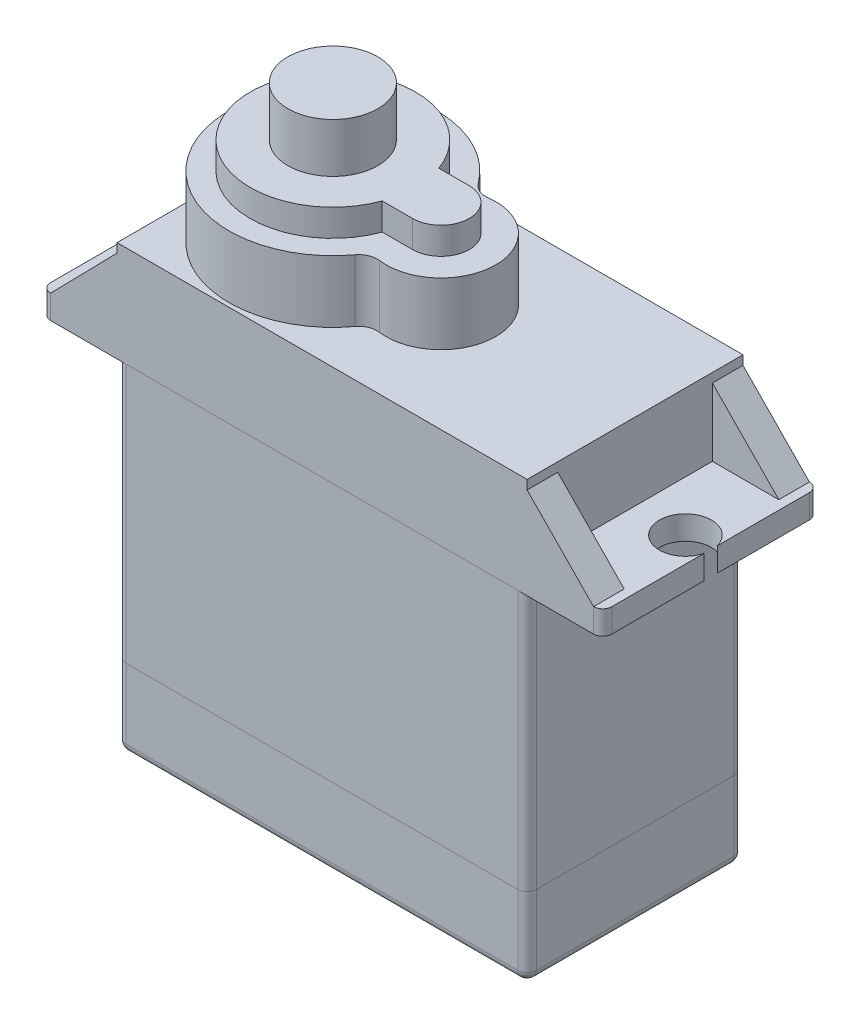
SolidWorks part; units mm, degrees
ref_plane "Front Plane" through (0, 0, 0) normal (0, 0, 1) x (1, 0, 0)
ref_plane "Top Plane" through (0, 0, 0) normal (0, 1, 0) x (1, 0, 0)
ref_plane "Right Plane" through (0, 0, 0) normal (1, 0, 0) x (0, 0, -1)
sketch "Sketch1" plane through (0, 0, 0) normal (0, 1, 0) x (1, 0, 0)
  line L1 (0, 0) -> (22.8, 0)
  line L2 (0, 0) -> (0, 12)
  line L3 (0, 12) -> (22.8, 12)
  line L4 (22.8, 0) -> (22.8, 12)
  dimension "D1" = 22.8
  dimension "D2" = 12
extrude "Boss-Extrude1" add sketch "Sketch1" along normal blind 4.4
sketch "Sketch2" plane through (0, 4.4, 0) normal (0, 1, 0) x (1, 0, 0)
  line L1 (0, 0) -> (22.8, 0)
  line L2 (0, 0) -> (0, 12)
  line L3 (0, 12) -> (22.8, 12)
  line L4 (22.8, 0) -> (22.8, 12)
extrude "Boss-Extrude4" add sketch "Sketch2" along normal blind 14.4 separate body
sketch "Sketch5" plane through (0, 18.8, 0) normal (0, 1, 0) x (1, 0, 0)
  line L1 (0, 0) -> (22.8, 0)
  line L2 (0, 0) -> (0, 12)
  line L3 (0, 12) -> (22.8, 12)
  line L4 (22.8, 0) -> (22.8, 12)
extrude "Boss-Extrude6" add sketch "Sketch5" along normal blind 5.6 separate body
sketch "Sketch7" plane through (0, 0, 0) normal (-1, 0, 0) x (0, 0, 1)
  line L0 (-12, 24.4) -> (-12, 18.8) construction
  line L1 (-12, 18.8) -> (0, 18.8)
  line L2 (-12, 18.8) -> (-12, 20.1208)
  line L3 (-12, 20.1208) -> (0, 20.1208)
  line L4 (0, 18.8) -> (0, 20.1208)
  line L5 (0, 24.4) -> (0, 18.8) construction
  line L6 (-12, 18.8) -> (0, 18.8) construction
  dimension "D1" = 1.3208
extrude "Boss-Extrude9" add sketch "Sketch7" along normal blind 4.2
sketch "Sketch9" plane through (0, 0, 0) normal (0, 0, 1) x (1, 0, 0)
  line L0 (0, 23.892) -> (-3.692, 20.1208)
  line L1 (-4.2, 20.1208) -> (0, 20.1208) construction
  line L2 (0, 24.4) -> (0, 20.1208) construction
  dimension "D1" = 0.508
  dimension "D2" = 0.508
rib "Rib7" sketch "Sketch9" sketch "Sketch9" thickness 1.7018 extrusion direction parallel to sketch draft on no parameters "D1"=1.7018
ref_plane "Plane1" through (0, 0, -6) normal (0, 0, -1) x (-1, 0, 0)
mirror "Mirror1" about plane through (0, 0, -6) normal (0, 0, -1) of "Rib7"
sketch "Sketch10" plane through (0, 20.1208, 0) normal (0, 1, 0) x (1, 0, 0)
  line L0 (-4.2, 12) -> (-4.2, 0) construction
  line L1 (-4.2, 6) -> (-2.8, 6) construction
  line L2 (-4.2, 6.369) -> (-4.2, 5.631) construction
  line L3 (22.8, 12) -> (0, 12) construction
  line L4 (22.8, 12) -> (0, 12) construction
  line L5 (11.4, 12) -> (11.4, 0) construction
  circle A0 centre (-2.8, 6) radius 1.4478
  dimension "D1" = 2.8956
  dimension "D2" = 14.2
extrude "Cut-Extrude1" cut sketch "Sketch10" against normal up to next (1.3208 mm away)
ref_plane "Plane2" through (11.4, 0, 0) normal (-1, 0, 0) x (0, 0, 1)
mirror "Mirror2" about plane through (11.4, 0, 0) normal (-1, 0, 0) of "Cut-Extrude1", "Mirror1", "Rib7", "Boss-Extrude9"
sketch "Sketch11" plane through (0, 24.4, 0) normal (0, 1, 0) x (1, 0, 0)
  line L0 (0, 6) -> (22.8, 6) construction
  line L1 (0, 12) -> (0, 0) construction
  line L2 (22.8, 0) -> (22.8, 12) construction
  line L3 (0, 12) -> (6, 6) construction
  arc A0 (10.6532, 9.4261) -> (10.6532, 2.5739) centre (6, 6) ccw
  arc A1 (11.6053, 9.0214) -> (11.6053, 2.9786) centre (12.0071, 6) cw
  arc A2 (10.6532, 2.5739) -> (11.6053, 2.9786) centre (11.4714, 1.9715) cw
  arc A3 (10.6532, 9.4261) -> (11.6053, 9.0214) centre (11.4714, 10.0285) ccw
  point P13 (0.2215, 6)
  point P15 (15.0551, 6)
  point P16 (11.0096, 3.1199)
  point P19 (11.0096, 8.8801)
  dimension "D2" = 11.557
  dimension "D3" = 3.048
  dimension "D5" = 1.016
  dimension "D1" = 45
  dimension "D4" = 14.8336
extrude "Boss-Extrude10" add sketch "Sketch11" along normal blind 3.4544 separate body
fillet "Fillet1" radius 0.508 4 edges at (0, 11.6, -12) (0, 11.6, 0) (22.8, 11.6, 0) (22.8, 11.6, -12)
fillet "Fillet3" radius 0.508 4 edges at (-4.2, 19.4604, 0) (-4.2, 19.4604, -12) (27, 19.4604, -12) (27, 19.4604, 0)
sketch "Sketch12" plane through (0, 27.8544, 0) normal (0, 1, 0) x (1, 0, 0)
  line L0 (12.0071, 4.4252) -> (10.3193, 4.4252)
  line L1 (12.0071, 7.5748) -> (10.3193, 7.5748)
  arc A0 (10.6532, 9.4261) -> (10.6532, 2.5739) centre (6, 6) ccw construction
  arc A1 (10.6532, 9.4261) -> (10.6532, 2.5739) centre (6, 6) ccw construction
  arc A3 (11.6053, 2.9786) -> (11.6053, 9.0214) centre (12.0071, 6) ccw construction
  arc A4 (11.6053, 2.9786) -> (11.6053, 9.0214) centre (12.0071, 6) ccw construction
  arc A5 (12.0071, 4.4252) -> (12.0071, 7.5748) centre (12.0071, 6) ccw
  arc A6 (10.3193, 4.4252) -> (10.3193, 7.5748) centre (6, 6) cw
  dimension "D1" = 1.5748
  dimension "D2" = 4.5974
extrude "Boss-Extrude11" add sketch "Sketch12" along normal blind 1.4986
sketch "Sketch13" plane through (0, 29.353, 0) normal (0, 1, 0) x (1, 0, 0)
  arc A0 (10.3193, 7.5748) -> (10.3193, 4.4252) centre (6, 6) ccw construction
  arc A1 (10.3193, 7.5748) -> (10.3193, 4.4252) centre (6, 6) ccw construction
  circle A2 centre (6, 6) radius 2.5019
  dimension "D1" = 5.0038
extrude "Boss-Extrude12" add sketch "Sketch13" along normal blind 2.7432
sketch "Sketch14" plane through (0, 0, 0) normal (-1, 0, 0) x (0, 0, 1)
  line L0 (-12, 0) -> (0, 0) construction
  line L1 (-9.4417, 0) -> (-2.5583, 0)
  line L2 (-9.4417, 0) -> (-9.4417, 4.4)
  line L3 (-9.4417, 4.4) -> (-2.5583, 4.4)
  line L4 (-2.5583, 0) -> (-2.5583, 4.4)
  line L6 (-12, 4.4) -> (0, 4.4) construction
  point P9 (-6, 0)
  dimension "D1" = 6.8834
extrude "Boss-Extrude14" add sketch "Sketch14" along normal blind 0.4064
sketch "Sketch15" plane through (-0.4064, 0, 0) normal (-1, 0, 0) x (0, 0, 1)
  line L0 (-9.4417, 1.778) -> (-2.5583, 1.778) construction
  line L1 (-9.4417, 4.4) -> (-9.4417, 0) construction
  line L2 (-2.5583, 0) -> (-2.5583, 4.4) construction
  line L3 (-9.4417, 0) -> (-2.5583, 0) construction
  circle A0 centre (-6, 1.778) radius 0.5715
  circle A1 centre (-4.857, 1.778) radius 0.5715
  circle A2 centre (-7.143, 1.778) radius 0.5715
  dimension "D1" = 1.143
  dimension "D2" = 1.778
extrude "Boss-Extrude15" add sketch "Sketch15" along normal blind 1.27 separate body contours A0 | A1 | A2
fillet "Fillet4" radius 0.508 12 edges at (-0.4064, 0, -6) (11.4, 0, 0) (22.8, 0, -6) (11.4, 0, -12) (0, 2.2, 0) (22.8, 2.2, 0) (22.8, 2.2, -12) (0, 2.2, -12)
